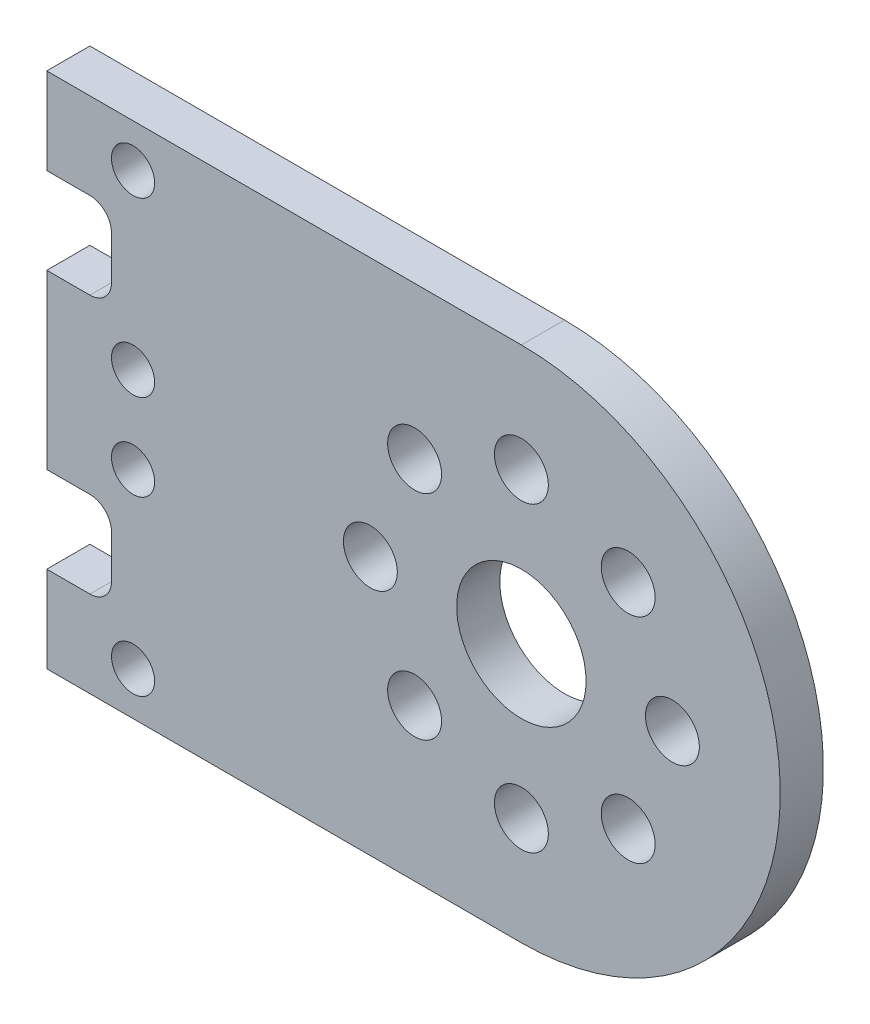
SolidWorks part; units mm, degrees
material "自訂玻璃纖維"
ref_plane "前基準面" through (0, 0, 0) normal (0, 0, 1) x (1, 0, 0)
ref_plane "上基準面" through (0, 0, 0) normal (0, 1, 0) x (1, 0, 0)
ref_plane "右基準面" through (0, 0, 0) normal (1, 0, 0) x (0, 0, -1)
sketch "草圖8" plane through (0, 0, 0) normal (0, 0, 1) x (1, 0, 0)
  line L0 (-25.4048, 11.8614) -> (-25.4048, 7.8614)
  line L1 (-25.4048, 11.8614) -> (-3.4048, 11.8614)
  line L2 (-3.4048, -12.1386) -> (-25.4048, -12.1386)
  line L3 (-25.4048, 7.8614) -> (-23.4048, 7.8614)
  line L4 (-25.4048, -8.1386) -> (-25.4048, -12.1386)
  line L5 (-23.4048, 3.8614) -> (-25.4048, 3.8614)
  line L6 (-25.4048, 3.8614) -> (-25.4048, -4.1386)
  line L7 (-22.4048, 6.8614) -> (-22.4048, 4.8614)
  line L8 (-23.4048, -4.1386) -> (-25.4048, -4.1386)
  line L9 (-22.4048, -7.1386) -> (-22.4048, -5.1386)
  line L10 (-25.4048, -8.1386) -> (-23.4048, -8.1386)
  arc A0 (-3.4048, 11.8614) -> (-3.4048, -12.1386) centre (-3.4048, -0.1386) cw
  circle A1 centre (-3.4048, 6.8614) radius 1.25
  circle A2 centre (1.545, 4.8111) radius 1.25
  circle A3 centre (-3.4048, -0.1386) radius 3
  circle A4 centre (3.5952, -0.1386) radius 1.25
  circle A5 centre (1.545, -5.0884) radius 1.25
  circle A6 centre (-3.4048, -7.1386) radius 1.25
  circle A7 centre (-8.3545, -5.0884) radius 1.25
  circle A8 centre (-10.4048, -0.1386) radius 1.25
  circle A9 centre (-8.3545, 4.8111) radius 1.25
  circle A10 centre (-21.4048, 9.8614) radius 1
  circle A11 centre (-21.4048, 1.8614) radius 1
  circle A12 centre (-21.4048, -2.1386) radius 1
  circle A13 centre (-21.4048, -10.1386) radius 1
  arc A14 (-23.4048, 7.8614) -> (-22.4048, 6.8614) centre (-23.4048, 6.8614) cw
  arc A15 (-23.4048, 3.8614) -> (-22.4048, 4.8614) centre (-23.4048, 4.8614) ccw
  arc A16 (-23.4048, -4.1386) -> (-22.4048, -5.1386) centre (-23.4048, -5.1386) cw
  arc A17 (-23.4048, -8.1386) -> (-22.4048, -7.1386) centre (-23.4048, -7.1386) ccw
  point P28 (-3.4048, -0.1386)
  point P30 (-4.4056, -0.9391)
  point P40 (-4.4056, -0.1386)
  dimension "D1" = 2.5
  dimension "D2" = 7
  dimension "D3" = 6
  dimension "D5" = 2
  dimension "D6" = 8
  dimension "D7" = 2
  dimension "D9" = 2
  dimension "D12" = 2
  dimension "D13" = 12
  dimension "D10" = 8
  dimension "D11" = 24
  dimension "D15" = 22
  dimension "D4" = 8
extrude "填料-伸長1" add sketch "草圖8" along normal blind 2
